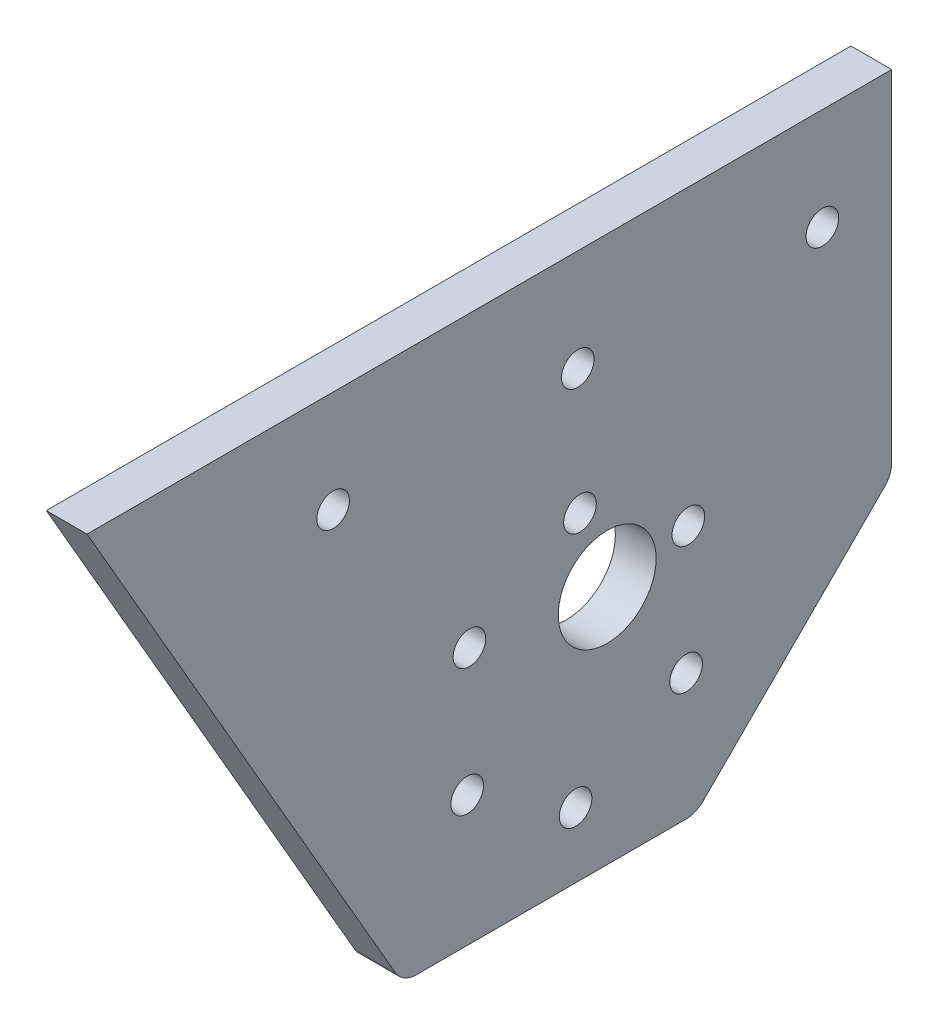
SolidWorks part; units mm, degrees
ref_plane "Front Plane" through (0, 0, 0) normal (0, 0, 1) x (1, 0, 0)
ref_plane "Top Plane" through (0, 0, 0) normal (0, 1, 0) x (1, 0, 0)
ref_plane "Right Plane" through (0, 0, 0) normal (1, 0, 0) x (0, 0, -1)
sketch "Sketch1" plane through (0, 0, 0) normal (1, 0, 0) x (0, 0, -1)
  line L0 (-70.1056, 25) -> (34.8944, 25) construction
  line L1 (-70.1056, 12.5) -> (34.8944, 12.5) construction
  line L2 (-70.1056, 12.5) -> (-70.1056, 37.5) construction
  line L3 (-70.1056, 37.5) -> (34.8944, 37.5) construction
  line L4 (34.8944, 12.5) -> (34.8944, 37.5) construction
  line L5 (-3.6056, -6) -> (0, 0) construction
  line L6 (14.8944, -6) -> (14.8944, 12.5) construction
  line L7 (34.8944, 36.5556) -> (34.8944, -4.2574)
  line L8 (9.6518, -29.5) -> (-23.3735, -29.5)
  line L9 (-25.9716, -28) -> (-63.788, 37.5)
  line L10 (-63.788, 37.5) -> (41.439, 154.3665) construction
  line L12 (-3.6056, -6) -> (9.6802, -13.9837) construction
  line L13 (-3.6056, -6) -> (-3.6056, 25) construction
  line L14 (50, 0) -> (50, 156.1863) construction
  line L15 (35.0422, 38.4328) -> (49.5493, 130.0272) construction
  line L16 (49.1097, 135.6126) -> (43.1332, 154.0064) construction
  line L17 (34.0158, -6.3787) -> (11.7731, -28.6213)
  line L18 (34.8944, 36.5556) -> (34.8944, 37.5)
  line L19 (34.8944, 37.5) -> (-63.788, 37.5)
  circle A0 centre (0, 0) radius 50 construction
  circle A1 centre (-3.6056, -6) radius 18.5 construction
  circle A2 centre (0, 0) radius 6
  circle A3 centre (9.6802, -13.9837) radius 2
  circle A4 centre (-3.8768, -21.4976) radius 2
  circle A5 centre (-17.1625, -13.5139) radius 2
  circle A6 centre (-16.8913, 1.9837) radius 2
  circle A7 centre (-3.3343, 9.4976) radius 2
  circle A8 centre (9.9514, 1.5139) radius 2
  circle A9 centre (-3.6056, 25) radius 2
  circle A10 centre (26.3944, 25) radius 2
  circle A11 centre (-33.6056, 25) radius 2
  arc A14 (49.1097, 135.6126) -> (49.5493, 130.0272) centre (37.6971, 131.9044) cw construction
  arc A15 (35.0422, 38.4328) -> (34.8944, 36.5556) centre (46.8944, 36.5556) ccw construction
  arc A16 (43.1332, 154.0064) -> (41.439, 154.3665) centre (42.1822, 153.6974) ccw construction
  arc A17 (34.8944, -4.2574) -> (34.0158, -6.3787) centre (31.8944, -4.2574) cw
  arc A18 (11.7731, -28.6213) -> (9.6518, -29.5) centre (9.6518, -26.5) cw
  arc A19 (-23.3735, -29.5) -> (-25.9716, -28) centre (-23.3735, -26.5) cw
  point P34 (-3.6056, -6)
  point P43 (34.8944, -29.5)
  point P45 (34.8944, -29.5)
  point P48 (-25.1056, -29.5)
  point P51 (50, 132.8727)
  point P58 (34.8944, -5.5)
  point P61 (10.8944, -29.5)
  point P64 (-25.1056, -29.5)
  dimension "D1" = 100
  dimension "D3" = 37
  dimension "D4" = 12
  dimension "D10" = 4
  dimension "D13" = 4
  dimension "D14" = 30
  dimension "D15" = 30
  dimension "D21" = 3
  dimension "D22" = 12
  dimension "D23" = 1
  dimension "D2" = 12.5
  dimension "D5" = 7
  dimension "D6" = 20
  dimension "D7" = 105
  dimension "D8" = 42
  dimension "D9" = 60
  dimension "D12" = 15.5
  dimension "D16" = 25
  dimension "D17" = 60
  dimension "D18" = 72
  dimension "D19" = 9
  dimension "D20" = 18
  dimension "D11" = 6
extrude "Boss-Extrude1" add sketch "Sketch1" along normal blind 5
